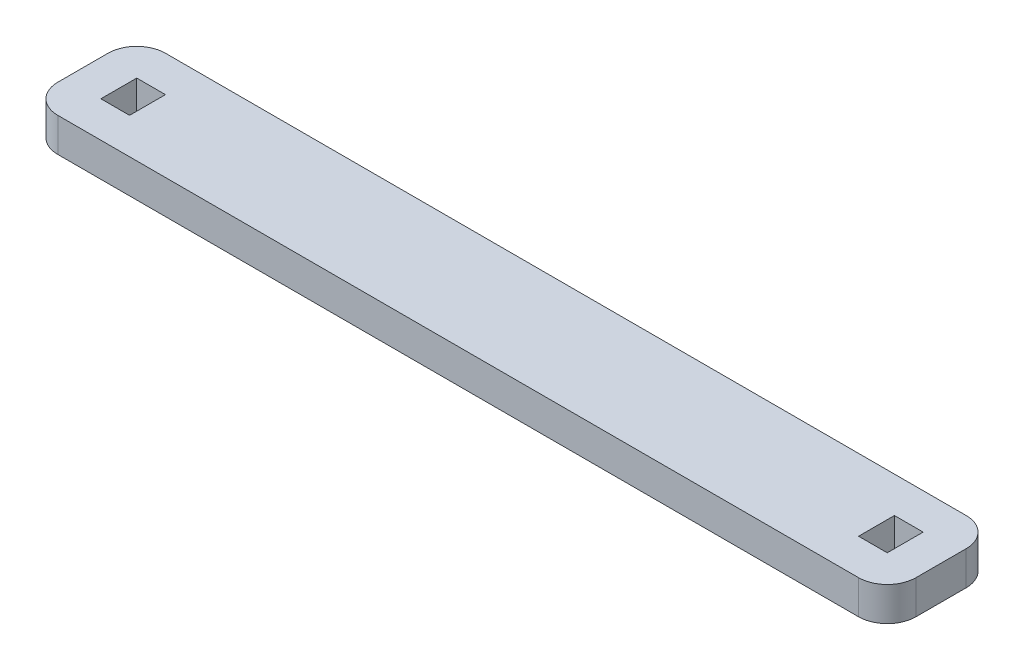
SolidWorks part; units mm, degrees
ref_plane "Front Plane" through (0, 0, 0) normal (0, 0, 1) x (1, 0, 0)
ref_plane "Top Plane" through (0, 0, 0) normal (0, 1, 0) x (1, 0, 0)
ref_plane "Right Plane" through (0, 0, 0) normal (1, 0, 0) x (0, 0, -1)
sketch "Sketch1" plane through (0, 0, 0) normal (0, 1, 0) x (1, 0, 0)
  line L0 (-33.528, 0) -> (33.528, 0) construction
  line L6 (37.973, -4.7625) -> (-37.973, -4.7625)
  line L7 (-32.258, -1.5875) -> (-34.798, -1.5875)
  line L8 (-32.258, -1.5875) -> (-32.258, 1.5875)
  line L9 (-32.258, 1.5875) -> (-34.798, 1.5875)
  line L10 (-34.798, -1.5875) -> (-34.798, 1.5875)
  line L11 (-32.258, -1.5875) -> (-34.798, 1.5875) construction
  line L12 (-32.258, 1.5875) -> (-34.798, -1.5875) construction
  line L13 (34.798, -1.5875) -> (32.258, -1.5875)
  line L14 (34.798, -1.5875) -> (34.798, 1.5875)
  line L15 (34.798, 1.5875) -> (32.258, 1.5875)
  line L16 (32.258, -1.5875) -> (32.258, 1.5875)
  line L17 (34.798, -1.5875) -> (32.258, 1.5875) construction
  line L18 (34.798, 1.5875) -> (32.258, -1.5875) construction
  line L19 (37.973, -4.7625) -> (37.973, 4.7625)
  line L20 (37.973, 4.7625) -> (-37.973, 4.7625)
  line L21 (-37.973, -4.7625) -> (-37.973, 4.7625)
  line L22 (37.973, -4.7625) -> (-37.973, 4.7625) construction
  line L23 (37.973, 4.7625) -> (-37.973, -4.7625) construction
  point P0 (0, 0)
  point P1 (0, 0)
  point P6 (-33.528, 0)
  point P11 (33.528, 0)
  dimension "D1" = 9.525
  dimension "D2" = 3.175
  dimension "D3" = 2.54
  dimension "D4" = 67.056
  dimension "D5" = 3.175
extrude "Boss-Extrude1" add sketch "Sketch1" along normal mid plane 3
fillet "Fillet1" radius 2.54 4 edges at (-37.973, 0, -4.7625) (37.973, 0, -4.7625) (37.973, 0, 4.7625) (-37.973, 0, 4.7625)
